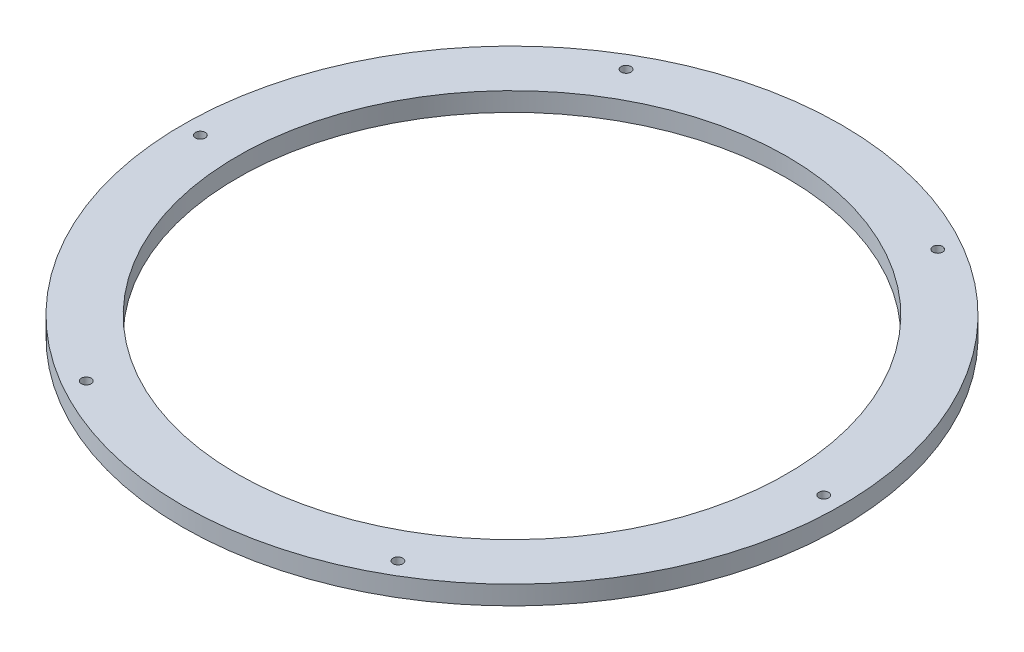
SolidWorks part; units mm, degrees
ref_plane "Спереди" through (0, 0, 0) normal (0, 0, 1) x (1, 0, 0)
ref_plane "Сверху" through (0, 0, 0) normal (0, 1, 0) x (1, 0, 0)
ref_plane "Справа" through (0, 0, 0) normal (1, 0, 0) x (0, 0, -1)
sketch "Эскиз1" plane through (0, 0, 0) normal (0, 1, 0) x (1, 0, 0)
  circle A0 centre (0, 0) radius 175
  circle A1 centre (0, 0) radius 146
  dimension "D1" = 292
  dimension "D2" = 350
extrude "Бобышка-Вытянуть1" add sketch "Эскиз1" along normal blind 10
sketch "Эскиз2" plane through (0, 10, 0) normal (0, 1, 0) x (1, 0, 0)
  circle A0 centre (0, 0) radius 165.5 construction
  circle A1 centre (0, 0) radius 175 construction
  circle A2 centre (-165.5, 0) radius 2.6
  dimension "D1" = 9.5
  dimension "D2" = 5.2
extrude "Вырез-Вытянуть1" cut sketch "Эскиз2" against normal through all
pattern_circular "Круговой массив1" count 6 over 360 about axis through (0, 0, 0) along (0, 1, 0) of "Вырез-Вытянуть1"
